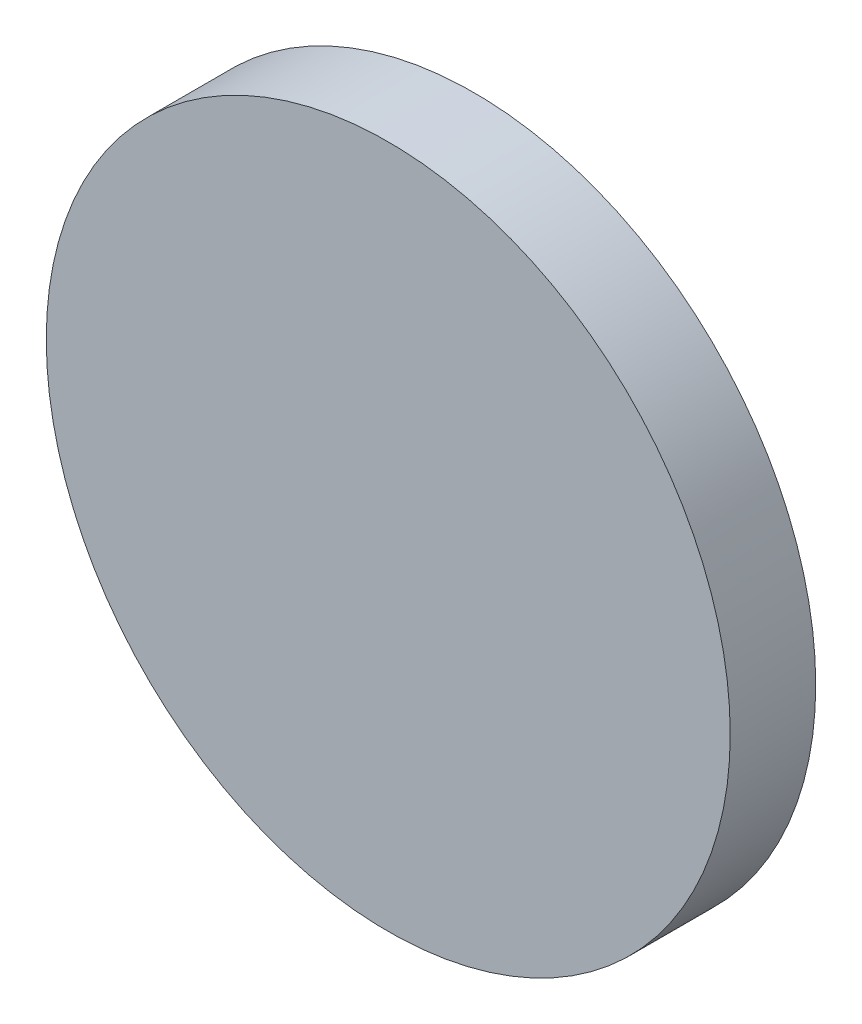
SolidWorks part; units mm, degrees
ref_plane "前视基准面" through (0, 0, 0) normal (0, 0, 1) x (1, 0, 0)
ref_plane "上视基准面" through (0, 0, 0) normal (0, 1, 0) x (1, 0, 0)
ref_plane "右视基准面" through (0, 0, 0) normal (1, 0, 0) x (0, 0, -1)
other "Configuration Table"
sketch "草图1" plane through (0, 0, 0) normal (0, 0, 1) x (1, 0, 0)
  circle A0 centre (0, 0) radius 20
extrude "凸台-拉伸1" add sketch "草图1" along normal blind 5 contours A0
